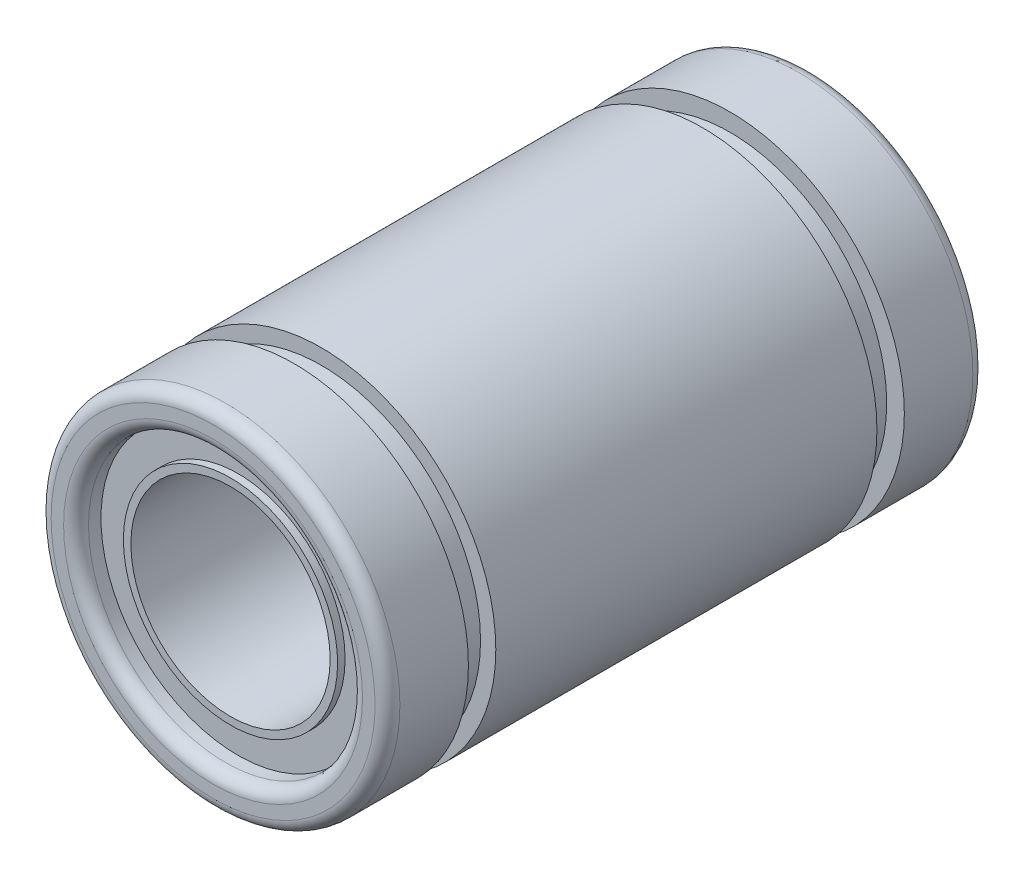
SolidWorks part; units mm, degrees
material "AISI 1020"
ref_plane "Front Plane" through (0, 0, 0) normal (0, 0, 1) x (1, 0, 0)
ref_plane "Top Plane" through (0, 0, 0) normal (0, 1, 0) x (1, 0, 0)
ref_plane "Right Plane" through (0, 0, 0) normal (1, 0, 0) x (0, 0, -1)
sketch "Sketch4" plane through (0, 0, 0) normal (1, 0, 0) x (0, 0, -1)
  line L0 (0, 0) -> (24, 0) construction
  line L1 (-0.139, 4) -> (23.861, 4)
  line L2 (23.861, 4) -> (23.861, 7)
  line L3 (23.861, 7) -> (20.611, 7)
  line L4 (20.611, 7) -> (20.611, 6.292)
  line L5 (20.611, 6.292) -> (19.511, 6.292)
  line L6 (19.511, 6.292) -> (19.511, 7)
  line L7 (19.511, 7) -> (4.211, 7)
  line L8 (4.211, 7) -> (4.211, 6.3869)
  line L9 (4.211, 6.3869) -> (3.111, 6.3869)
  line L10 (3.111, 6.3869) -> (3.111, 7)
  line L11 (3.111, 7) -> (-0.139, 7)
  line L12 (-0.139, 7) -> (-0.139, 4)
  dimension "D1" = 24
  dimension "D2" = 1.1
  dimension "D3" = 1.1
  dimension "D4" = 3.25
  dimension "D5" = 3.25
  dimension "D6" = 4
  dimension "D7" = 7
  dimension "D8" = 7
revolve "Revolve1" add sketch "Sketch4" angle 360 about L0
fillet "Fillet1" radius 0.5 2 edges at (7, 0, -23.861) (7, 0, 0.139)
sketch "Sketch5" plane through (0, 0, 0.139) normal (0, 0, 1) x (1, 0, 0)
  circle A2 centre (0, 0) radius 5.5
  circle A3 centre (0, 0) radius 5.5
  dimension "D1" = 1
extrude "Cut-Extrude1" cut sketch "Sketch5" against normal blind 1
fillet "Fillet2" radius 0.5 1 edges at (5.5, 0, 0.139)
sketch "Sketch6" plane through (0, 0, -23.861) normal (0, 0, -1) x (-1, 0, 0)
  circle A2 centre (0, 0) radius 5.5
  circle A3 centre (0, 0) radius 5.5
  dimension "D1" = 1
extrude "Cut-Extrude2" cut sketch "Sketch6" against normal blind 1
fillet "Fillet3" radius 0.5 1 edges at (-5.5, 0, -23.861)
sketch "Sketch8" plane through (0, 0, -0.861) normal (0, 0, 1) x (1, 0, 0)
  circle A1 centre (0, 0) radius 4
  circle A2 centre (0, 0) radius 4.3
  circle A3 centre (0, 0) radius 4.3
  dimension "D1" = 1.2
extrude "Boss-Extrude4" add sketch "Sketch8" along normal blind 0.3
sketch "Sketch9" plane through (0, 0, -22.861) normal (0, 0, -1) x (-1, 0, 0)
  circle A1 centre (0, 0) radius 4
  circle A2 centre (0, 0) radius 4.3
  circle A3 centre (0, 0) radius 4.3
  dimension "D1" = 0.3
extrude "Boss-Extrude5" add sketch "Sketch9" along normal blind 0.3
